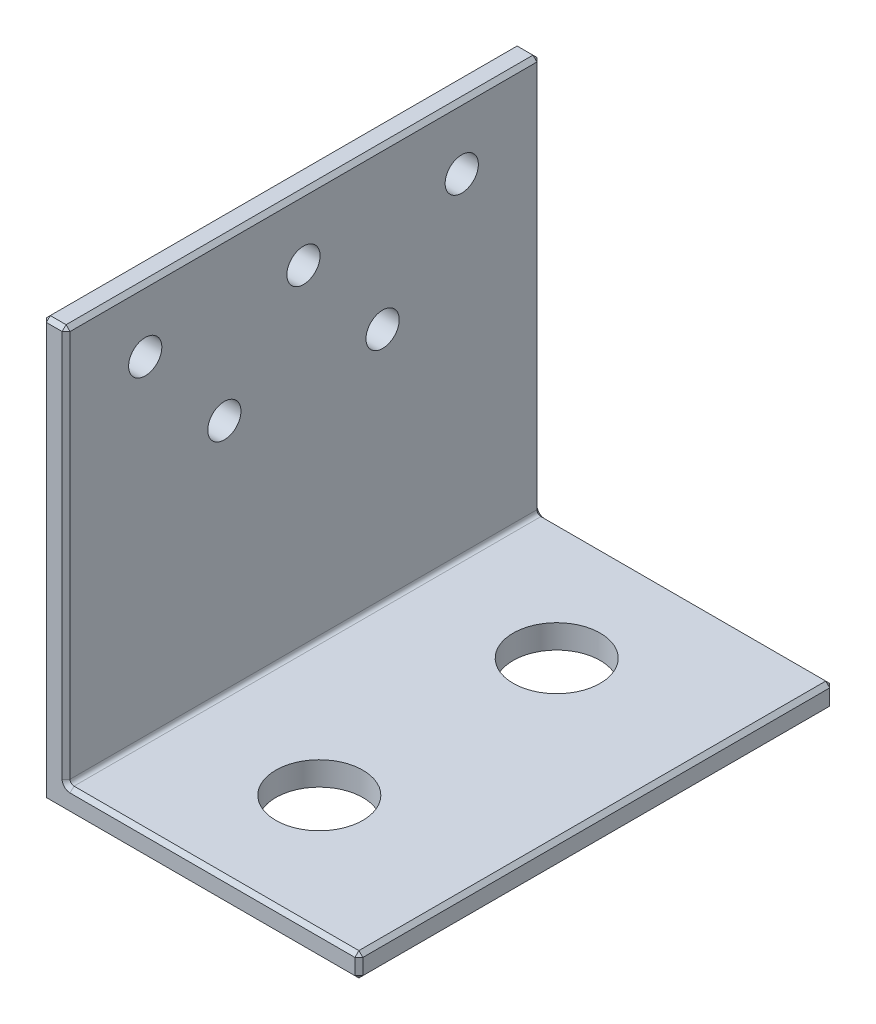
SolidWorks part; units mm, degrees
material "1.0553 (S355J0)"
ref_plane "Płaszczyzna przednia" through (0, 0, 0) normal (0, 0, 1) x (1, 0, 0)
ref_plane "Płaszczyzna górna" through (0, 0, 0) normal (0, 1, 0) x (1, 0, 0)
ref_plane "Płaszczyzna prawa" through (0, 0, 0) normal (1, 0, 0) x (0, 0, -1)
sketch "Szkic1" plane through (0, 0, 0) normal (0, 0, 1) x (1, 0, 0)
  line L0 (0, 3) -> (0, 53)
  line L1 (0, 0) -> (40, 0)
  line L2 (0, 0) -> (0, 3)
  line L3 (3, 3) -> (40, 3)
  line L4 (40, 0) -> (40, 3)
  line L5 (0, 53) -> (3, 53)
  line L6 (3, 53) -> (3, 3)
  dimension "D1" = 3
  dimension "D2" = 3
  dimension "D3" = 50
  dimension "D4" = 40
extrude "Dodanie-wyciągnięcie1" add sketch "Szkic1" along normal blind 60
hole_wizard "Otwory ustalające Ø1.0mm1" positions "Szkic2" profile "Szkic3" hole size "Ø1.0" standard "ISO"
sketch "Szkic2" plane through (0, 3, 0) normal (0, 1, 0) x (1, 0, 0)
  line L0 (40, -60) -> (3, -60) construction
  line L1 (40, 0) -> (3, 0) construction
  line L2 (40, -60) -> (40, 0) construction
  point P0 (20, -45)
  point P2 (20, -15)
  dimension "D1" = 15
  dimension "D2" = 15
  dimension "D3" = 20
sketch "Szkic3" plane through (20, 3, 45) normal (1, 0, 0) x (0, 0, 1)
  line L0 (0, 0) -> (0, 25.5547)
  line L1 (0, 25.5547) -> (5.5, 22.25)
  line L2 (5.5, 22.25) -> (5.5, 0)
  line L5 (5.5, 0) -> (0, 0)
  line L10 (0, 25.5547) -> (-5.5, 22.25) construction
  line L11 (0, -6.35) -> (0, 107.95) construction
  dimension "Średnica otworu" = 11
  dimension "Głębokość otworu" = 22.25
  dimension "Kąt wiertła" = 118
hole_wizard "Otwór gwintowany M51" positions "Szkic4" profile "Szkic5" tap size "M5" standard "ISO"
sketch "Szkic4" plane through (3, 0, 0) normal (1, 0, 0) x (0, 0, -1)
  line L0 (-60, 53) -> (0, 53) construction
  line L1 (0, 3) -> (0, 53) construction
  point P0 (-50, 45)
  point P2 (-40, 33)
  point P4 (-30, 45)
  point P6 (-20, 33)
  point P8 (-10, 45)
  dimension "D1" = 20
  dimension "D2" = 20
  dimension "D3" = 12
  dimension "D4" = 8
  dimension "D5" = 10
  dimension "D6" = 10
  dimension "D7" = 10
sketch "Szkic5" plane through (3, 45, 50) normal (0, 1, 0) x (0, 0, -1)
  line L0 (0, 0) -> (0, 15.2618)
  line L1 (0, 15.2618) -> (2.1, 14)
  line L2 (2.1, 14) -> (2.1, 0)
  line L5 (2.1, 0) -> (0, 0)
  line L10 (0, 15.2618) -> (-2.1, 14) construction
  line L11 (0, -6.35) -> (0, 107.95) construction
  dimension "Średnica wiertła gwintu" = 4.2
  dimension "Głębokość otworu gwintowanego" = 14
  dimension "Kąt wiertła" = 118
cosmetic thread "Gwint otworu1" parameters "D1"=10, "D2"=5
cosmetic thread "Gwint otworu2" parameters "D1"=10, "D2"=5
cosmetic thread "Gwint otworu3" parameters "D1"=10, "D2"=5
cosmetic thread "Gwint otworu4" parameters "D1"=10, "D2"=5
cosmetic thread "Gwint otworu5" parameters "D1"=10, "D2"=5
fillet "Zaokrąglenie1" radius 0.5 1 edges at (3, 3, 30)
chamfer "Sfazowanie3" distance 0.5 angle 45 19 edges at (0, 26.5, 60) (3, 53, 30) (1.5, 53, 60) (0, 53, 30) (1.5, 53, 0) (0, 0, 30) (0, 26.5, 0) (20, 0, 0) (40, 0, 30) (20, 0, 60) (40, 1.5, 60) (40, 1.5, 0) (3, 28.25, 0) (3.1464, 3.1464, 0) (21.75, 3, 0) (40, 3, 30) (3, 28.25, 60) (3.1464, 3.1464, 60) (21.75, 3, 60)
equation "\"D2@Szkic4\"=\"D1@Szkic4\""
